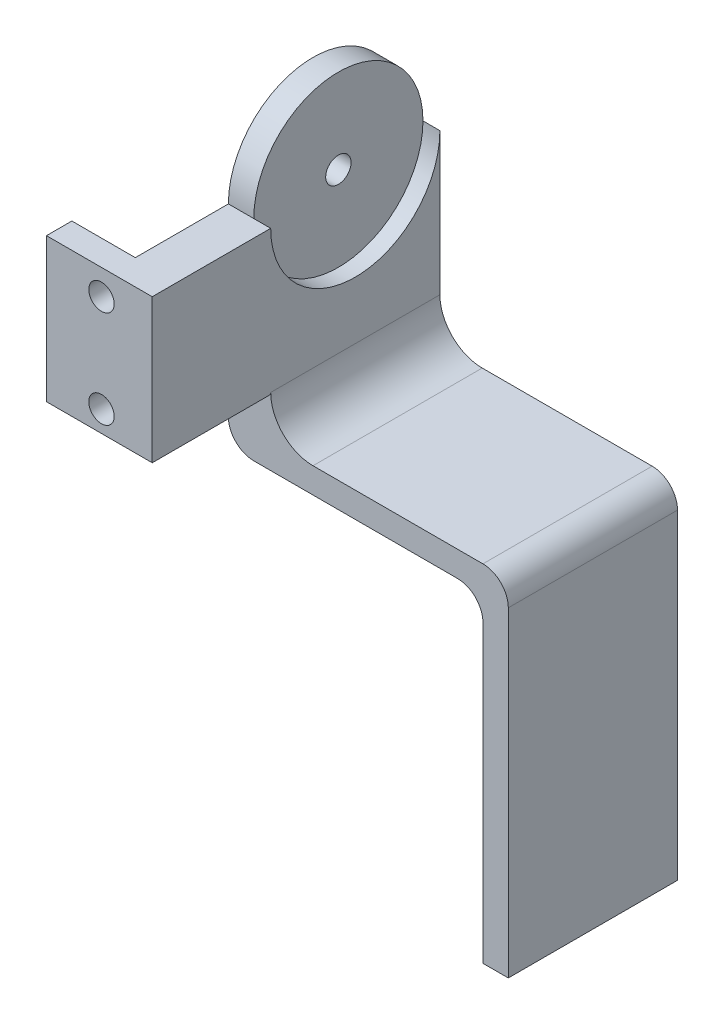
SolidWorks part; units mm, degrees
ref_plane "Front Plane" through (0, 0, 0) normal (0, 0, 1) x (1, 0, 0)
ref_plane "Top Plane" through (0, 0, 0) normal (0, 1, 0) x (1, 0, 0)
ref_plane "Right Plane" through (0, 0, 0) normal (1, 0, 0) x (0, 0, -1)
sketch "Sketch1" plane through (0, 0, 0) normal (0, 0, 1) x (1, 0, 0)
  line L7 (-3, -6) -> (-3, -40.8915)
  line L10 (0, -3) -> (0, -40.8915)
  line L11 (-3, -40.8915) -> (0, -40.8915)
  line L12 (-30.0845, -3) -> (-6, -3)
  line L14 (-3, 0) -> (-27.0845, 0)
  line L18 (-33.0845, 31.8) -> (-30.0845, 31.8)
  line L21 (-30.0845, 31.8) -> (-30.0845, 3)
  line L22 (-33.0845, 31.8) -> (-33.0845, 0)
  line L23 (-18.8756, 21.8) -> (-37.8172, 21.8) construction
  arc A0 (-27.0845, 0) -> (-30.0845, 3) centre (-27.0845, 3) cw
  arc A1 (-30.0845, -3) -> (-33.0845, 0) centre (-30.0845, 0) cw
  arc A2 (-3, -6) -> (-6, -3) centre (-6, -6) ccw
  arc A3 (0, -3) -> (-3, 0) centre (-3, -3) ccw
  point P15 (-33.0845, -3)
  point P18 (-3, -3)
  point P21 (0, 0)
  dimension "D1" = 34.8
  dimension "D8" = 3
  dimension "D9" = 3
  dimension "D10" = 3
  dimension "D2" = 3
  dimension "D3" = 30.0845
  dimension "D4" = 40.8915
  dimension "D5" = 3
  dimension "D6" = 10
  dimension "D7" = 3
extrude "Boss-Extrude1" add sketch "Sketch1" along normal blind 20
sketch "Sketch2" plane through (-30.0845, 0, 0) normal (1, 0, 0) x (0, 0, -1)
  line L0 (-20, 31.8) -> (0, 31.8) construction
  line L1 (-20, 3) -> (-20, 31.8) construction
  line L6 (0, 3) -> (0, 31.8)
  line L7 (0, 31.8) -> (-20, 31.8)
  line L8 (-20, 31.8) -> (-20, 3)
  line L9 (-20, 3) -> (0, 3)
  line L10 (0, 21.8) -> (0, 31.8)
  line L11 (0, 31.8) -> (-20, 31.8)
  line L12 (-20, 31.8) -> (-20, 21.8)
  line L14 (-20, 3) -> (0, 3)
  arc A0 (0, 21.8) -> (-20, 21.8) centre (-10, 21.8) ccw
  line M6 (0, 3) -> (0, 31.8)
  line M7 (0, 31.8) -> (-20, 31.8)
  line M8 (-20, 31.8) -> (-20, 3)
  dimension "D3" = 20
  dimension "D1" = 10
  dimension "D2" = 10
  dimension "D4" = 0
extrude "Cut-Extrude1" cut sketch "Sketch2" against normal blind 3 contours A0 M6 M7 | A0 L11 M8
sketch "Sketch3" plane through (0, 0, 20) normal (0, 0, 1) x (1, 0, 0)
  line L0 (-30.0858, 4.8) -> (-40.6658, 4.8) construction
  line L1 (-29.2769, 4.8) -> (-40.6658, 4.8)
sketch "Sketch4" plane through (0, 0, 20) normal (0, 0, 1) x (1, 0, 0)
  line L0 (-29.2769, 4.8) -> (-40.6658, 4.8) construction
  line L1 (-33.0845, 21.8) -> (-30.0845, 21.8)
  line L2 (-33.0845, 21.8) -> (-33.0845, 4.8)
  line L3 (-33.0845, 4.8) -> (-30.0845, 4.8)
  line L4 (-30.0845, 21.8) -> (-30.0845, 4.8)
  line L5 (-33.0845, 21.8) -> (-33.0845, 0) construction
  line L6 (-30.0845, 3) -> (-30.0845, 21.8) construction
  dimension "D1" = 17
  dimension "D2" = 3
extrude "Boss-Extrude2" add sketch "Sketch4" along normal blind 14
sketch "Sketch6" plane through (-33.0845, 0, 0) normal (-1, 0, 0) x (0, 0, 1)
  line L0 (34, 4.8) -> (34, 21.8)
  line L1 (34, 21.8) -> (31, 21.8)
  line L2 (34, 21.8) -> (20, 21.8) construction
  line L3 (31, 21.8) -> (31, 4.8)
  line L4 (34, 4.8) -> (20, 4.8) construction
  line L5 (31, 4.8) -> (34, 4.8)
  dimension "D1" = 3
extrude "Boss-Extrude3" add sketch "Sketch6" along normal blind 7.5
sketch "Sketch7" plane through (0, 0, 31) normal (0, 0, -1) x (-1, 0, 0)
  line L0 (40.5845, 4.8) -> (33.0845, 4.8) construction
  line L1 (33.0845, 21.8) -> (33.0845, 4.8) construction
  circle A0 centre (34.0845, 18.8) radius 1.5
  circle A1 centre (34.0845, 7.3) radius 1.5
  dimension "D4" = 3
  dimension "D6" = 3
  dimension "D1" = 2.5
  dimension "D2" = 1
  dimension "D5" = 11.5
extrude "Cut-Extrude3" cut sketch "Sketch7" against normal blind 7.5
sketch "Sketch8" plane through (-33.0845, 0, 0) normal (-1, 0, 0) x (0, 0, 1)
  line L0 (0, 21.8) -> (0, 0) construction
  line L2 (31, 4.8) -> (20, 4.8) construction
  circle A1 centre (10, 21.8) radius 1.5
  dimension "D3" = 3
  dimension "D1" = 10
  dimension "D2" = 17
extrude "Cut-Extrude4" cut sketch "Sketch8" against normal blind 10
sketch "Sketch10" plane through (0, 0, 31) normal (0, 0, -1) x (-1, 0, 0)
  circle A0 centre (34.0845, 7.3) radius 3
  circle A1 centre (34.0845, 18.8) radius 3
  dimension "D1" = 6
  dimension "D2" = 6
extrude "Cut-Extrude6" cut sketch "Sketch10" along normal blind 8
ref_plane "Plane1" through (0, 13.3, 0) normal (0, 1, 0) x (1, 0, 0)
sketch "Sketch11" plane through (0, 13.3, 0) normal (0, 1, 0) x (1, 0, 0)
  line L0 (-33.0845, -25.5) -> (-33.0845, -31)
  line L1 (-33.0845, -31) -> (-33.0845, -20) construction
  line L2 (-33.0845, -31) -> (-40.5845, -31)
  line L3 (-40.5845, -31) -> (-33.0845, -25.5)
extrude "Boss-Extrude4" add sketch "Sketch11" along normal blind 2 and the other way blind 2
sketch "Sketch12" plane through (-30.0845, 0, 0) normal (1, 0, 0) x (0, 0, -1)
  line L0 (-20, 4.8) -> (-20, 21.8)
  line L6 (-20, 21.8) -> (-34, 21.8)
  line L7 (-34, 21.8) -> (-34, 4.8)
  line L8 (-34, 4.8) -> (-20, 4.8)
  line L9 (-20, 4.8) -> (-20, 3)
  line L10 (-20, 3) -> (0, 3)
  line L11 (0, 3) -> (0, 21.8)
  line L12 (-20, 21.8) -> (-34, 21.8)
  line L13 (-34, 21.8) -> (-34, 4.8)
  line L14 (-34, 4.8) -> (-20, 4.8)
  arc A1 (0, 21.8) -> (-20, 21.8) centre (-10, 21.8) ccw
  dimension "D1" = 0
extrude "Boss-Extrude5" add sketch "Sketch12" along normal blind 2
sketch "Sketch15" plane through (-30.0845, 0, 0) normal (1, 0, 0) x (0, 0, -1)
  line L0 (0, 3) -> (0, 21.8) construction
  line L2 (0, 21.8) -> (0, 0)
  line L3 (0, 0) -> (-20, 0)
  line L4 (-20, 21.8) -> (-20, 0)
  line L5 (-20, 3) -> (-20, 4.8) construction
  line L6 (-20, 0) -> (0, 0) construction
  arc A5 (-20, 21.8) -> (0, 21.8) centre (-10, 21.8) ccw
  arc A6 (0, 21.8) -> (-20, 21.8) centre (-10, 21.8) ccw construction
  dimension "D1" = 20
extrude "Boss-Extrude6" add sketch "Sketch15" along normal up to vertex
sketch "Sketch16" plane through (0, 0, 0) normal (0, 0, -1) x (-1, 0, 0)
  line L0 (3, 0) -> (27.0845, 0) construction
  line L1 (28.0845, 0.1716) -> (28.0845, 21.8) construction
  line L3 (28.0845, 0) -> (23.0845, 0)
  line L4 (28.0845, 0) -> (28.0845, 5)
  arc A0 (23.0845, 0) -> (28.0845, 5) centre (23.0845, 5) ccw
  dimension "D1" = 10
extrude "Boss-Extrude7" add sketch "Sketch16" against normal blind 20
